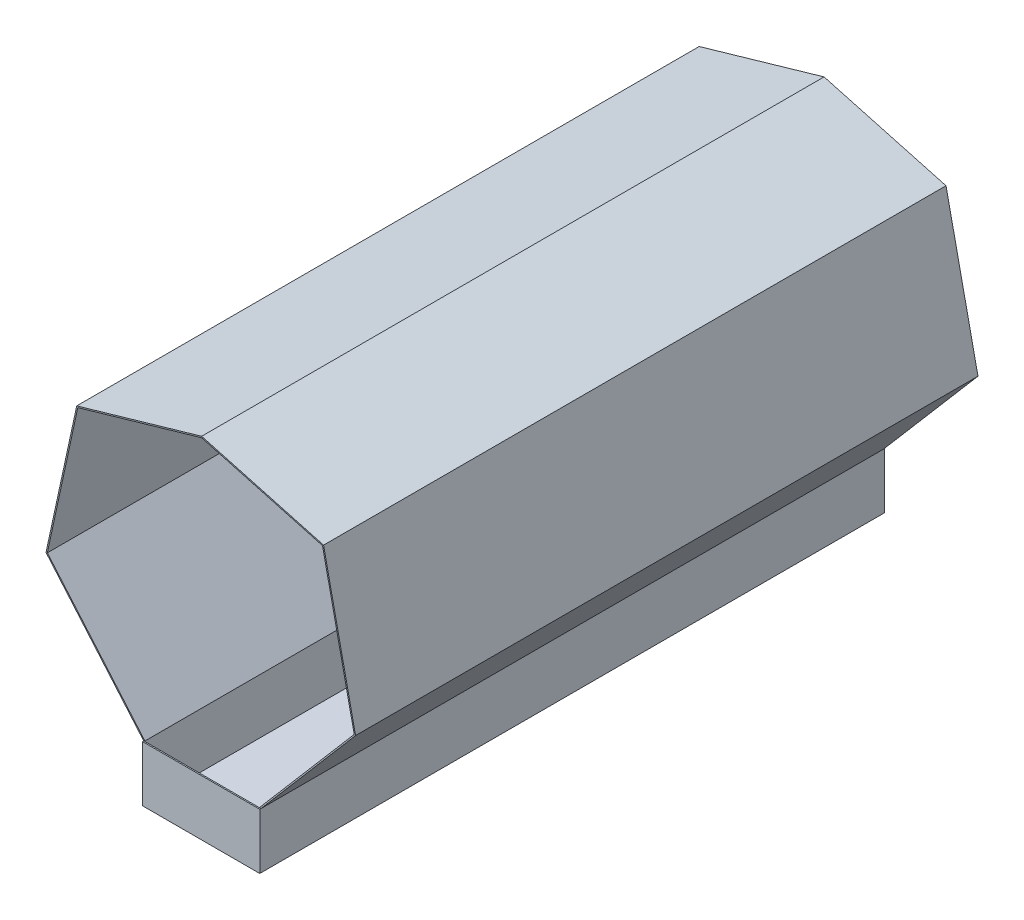
SolidWorks part; units mm, degrees
ref_plane "Front Plane" through (0, 0, 0) normal (0, 0, 1) x (1, 0, 0)
ref_plane "Top Plane" through (0, 0, 0) normal (0, 1, 0) x (1, 0, 0)
ref_plane "Right Plane" through (0, 0, 0) normal (1, 0, 0) x (0, 0, -1)
sketch "Sketch2" plane through (0, 0, 0) normal (0, 0, 1) x (1, 0, 0)
  line L1 (1911.8875, 22.2438) -> (1911.8875, 462.8089)
  line L2 (1911.8875, 462.8089) -> (2670.631, 1349.3407)
  line L3 (2670.631, 1349.3407) -> (2416.1061, 2535.1452)
  line L5 (2416.1061, 2535.1452) -> (1445.1079, 2800.1608)
  line L6 (1445.1079, 2800.1608) -> (450.1379, 2512.3893)
  line L8 (450.1379, 2512.3893) -> (205.652, 1379.9594)
  line L10 (205.652, 1379.9594) -> (989.2011, 462.8089)
  line L11 (989.2011, 462.8089) -> (989.2011, 22.2438)
  line L12 (989.2011, 22.2438) -> (1911.8875, 22.2438)
  point P0 (989.2011, 462.8089)
extrude "Extrude-Thin1" add sketch "Sketch2" along normal blind 5000 thin contours L8 L10 L11 L12 L1 L2 L3 L5 L6
sketch "Sketch3" plane through (0, 0, 5000) normal (0, 0, 1) x (1, 0, 0)
  line L1 (979.2011, 12.2438) -> (1921.8875, 12.2438)
  line L2 (979.2011, 12.2438) -> (979.2011, 459.1139)
  line L3 (979.2011, 459.1139) -> (1921.8875, 459.1139)
  line L4 (1921.8875, 12.2438) -> (1921.8875, 459.1139)
extrude "Boss-Extrude1" add sketch "Sketch3" along normal blind 10
sketch "Sketch4" plane through (0, 0, 0) normal (0, 0, -1) x (-1, 0, 0)
  line L1 (-1921.8875, 12.2438) -> (-979.2011, 12.2438)
  line L2 (-1921.8875, 12.2438) -> (-1921.8875, 459.1189)
  line L3 (-1921.8875, 459.1189) -> (-979.2011, 459.1189)
  line L4 (-979.2011, 12.2438) -> (-979.2011, 459.1189)
extrude "Boss-Extrude2" add sketch "Sketch4" along normal blind 10
sketch "Sketch5" plane through (0, 0, 5000) normal (0, 0, 1) x (1, 0, 0)
  line L0 (989.2011, 462.8089) -> (205.652, 1379.9594)
  line L1 (205.652, 1379.9594) -> (450.1379, 2512.3893)
  line L2 (450.1379, 2512.3893) -> (1445.1079, 2800.1608)
  line L3 (1445.1079, 2800.1608) -> (2416.1061, 2535.1452)
  line L4 (2416.1061, 2535.1452) -> (2670.631, 1349.3407)
  line L5 (2670.631, 1349.3407) -> (1911.8875, 462.8089)
  line L6 (1911.8875, 462.8089) -> (989.2011, 462.8089)
extrude "Boss-Extrude5" add sketch "Sketch5" along normal blind 500 draft 20 separate body contours L6 L0 L1 L2 L3 L4 L5 draft outward yes
other "DeleteFace3" face at (1440.9829, 1645.5918, 5500)
other "DeleteFace4" face at (1441.2462, 1643.2305, 5000)
